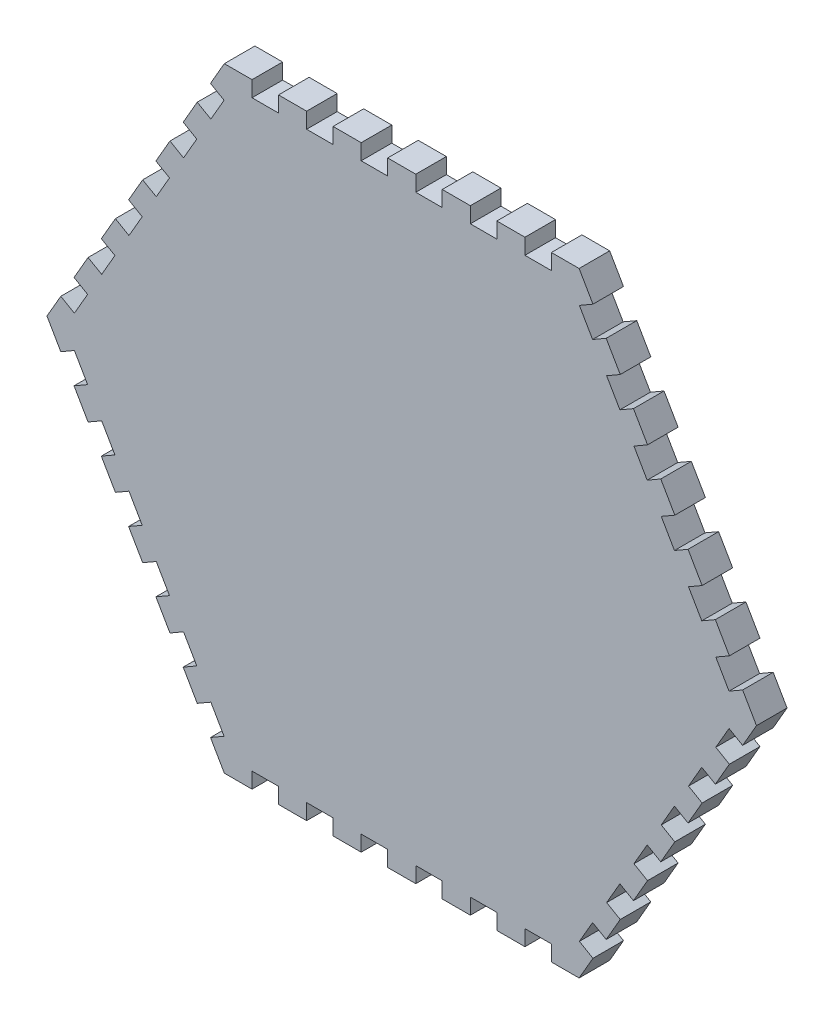
SolidWorks part; units mm, degrees
ref_plane "Piano frontale" through (0, 0, 0) normal (0, 0, 1) x (1, 0, 0)
ref_plane "Piano superiore" through (0, 0, 0) normal (0, 1, 0) x (1, 0, 0)
ref_plane "Piano destro" through (0, 0, 0) normal (1, 0, 0) x (0, 0, -1)
sketch "Schizzo1" plane through (0, 0, 0) normal (0, 0, 1) x (1, 0, 0)
  line L0 (-17.425, 53.4167) -> (-17.425, 56.2917)
  line L1 (32.5, 56.2917) -> (27.425, 56.2917)
  line L2 (-32.5, 56.2917) -> (-35.0375, 51.8966)
  line L3 (-65, 0) -> (-62.4625, -4.3951)
  line L4 (-32.5, -56.2917) -> (-27.425, -56.2917)
  line L5 (32.5, -56.2917) -> (35.0375, -51.8966)
  line L6 (65, 0) -> (62.4625, 4.3951)
  line L7 (-27.425, 53.4167) -> (-22.575, 53.4167)
  line L8 (-27.425, 53.4167) -> (-27.425, 56.2917)
  line L9 (-17.425, 56.2917) -> (-22.575, 56.2917)
  line L10 (-22.575, 53.4167) -> (-22.575, 56.2917)
  line L11 (-27.425, 53.4167) -> (-22.575, 56.2917) construction
  line L12 (-27.425, 56.2917) -> (-22.575, 53.4167) construction
  line L13 (-17.425, 53.4167) -> (-12.575, 53.4167)
  line L14 (-12.575, 53.4167) -> (-12.575, 56.2917)
  line L15 (-7.425, 53.4167) -> (-7.425, 56.2917)
  line L16 (-7.425, 53.4167) -> (-2.575, 53.4167)
  line L17 (-2.575, 53.4167) -> (-2.575, 56.2917)
  line L18 (2.575, 53.4167) -> (2.575, 56.2917)
  line L19 (2.575, 53.4167) -> (7.425, 53.4167)
  line L20 (7.425, 53.4167) -> (7.425, 56.2917)
  line L21 (12.575, 53.4167) -> (12.575, 56.2917)
  line L22 (12.575, 53.4167) -> (17.425, 53.4167)
  line L23 (17.425, 53.4167) -> (17.425, 56.2917)
  line L24 (22.575, 53.4167) -> (22.575, 56.2917)
  line L25 (22.575, 53.4167) -> (27.425, 53.4167)
  line L26 (27.425, 53.4167) -> (27.425, 56.2917)
  line L27 (32.5477, 50.4591) -> (35.0375, 51.8966)
  line L28 (32.5477, 50.4591) -> (34.9727, 46.2588)
  line L29 (34.9727, 46.2588) -> (37.4625, 47.6963)
  line L30 (37.5477, 41.7988) -> (40.0375, 43.2363)
  line L31 (37.5477, 41.7988) -> (39.9727, 37.5986)
  line L32 (39.9727, 37.5986) -> (42.4625, 39.0361)
  line L33 (42.5477, 33.1386) -> (45.0375, 34.5761)
  line L34 (42.5477, 33.1386) -> (44.9727, 28.9383)
  line L35 (44.9727, 28.9383) -> (47.4625, 30.3758)
  line L36 (47.5477, 24.4783) -> (50.0375, 25.9158)
  line L37 (47.5477, 24.4783) -> (49.9727, 20.2781)
  line L38 (49.9727, 20.2781) -> (52.4625, 21.7156)
  line L39 (52.5477, 15.8181) -> (55.0375, 17.2556)
  line L40 (52.5477, 15.8181) -> (54.9727, 11.6178)
  line L41 (54.9727, 11.6178) -> (57.4625, 13.0553)
  line L42 (57.5477, 7.1578) -> (60.0375, 8.5953)
  line L43 (57.5477, 7.1578) -> (59.9727, 2.9576)
  line L44 (59.9727, 2.9576) -> (62.4625, 4.3951)
  line L45 (59.9727, -2.9576) -> (62.4625, -4.3951)
  line L46 (59.9727, -2.9576) -> (57.5477, -7.1578)
  line L47 (57.5477, -7.1578) -> (60.0375, -8.5953)
  line L48 (54.9727, -11.6178) -> (57.4625, -13.0553)
  line L49 (54.9727, -11.6178) -> (52.5477, -15.8181)
  line L50 (52.5477, -15.8181) -> (55.0375, -17.2556)
  line L51 (49.9727, -20.2781) -> (52.4625, -21.7156)
  line L52 (49.9727, -20.2781) -> (47.5477, -24.4783)
  line L53 (47.5477, -24.4783) -> (50.0375, -25.9158)
  line L54 (44.9727, -28.9383) -> (47.4625, -30.3758)
  line L55 (44.9727, -28.9383) -> (42.5477, -33.1386)
  line L56 (42.5477, -33.1386) -> (45.0375, -34.5761)
  line L57 (39.9727, -37.5986) -> (42.4625, -39.0361)
  line L58 (39.9727, -37.5986) -> (37.5477, -41.7988)
  line L59 (37.5477, -41.7988) -> (40.0375, -43.2363)
  line L60 (34.9727, -46.2588) -> (37.4625, -47.6963)
  line L61 (34.9727, -46.2588) -> (32.5477, -50.4591)
  line L62 (32.5477, -50.4591) -> (35.0375, -51.8966)
  line L63 (27.425, -53.4167) -> (27.425, -56.2917)
  line L64 (27.425, -53.4167) -> (22.575, -53.4167)
  line L65 (22.575, -53.4167) -> (22.575, -56.2917)
  line L66 (17.425, -53.4167) -> (17.425, -56.2917)
  line L67 (17.425, -53.4167) -> (12.575, -53.4167)
  line L68 (12.575, -53.4167) -> (12.575, -56.2917)
  line L69 (7.425, -53.4167) -> (7.425, -56.2917)
  line L70 (7.425, -53.4167) -> (2.575, -53.4167)
  line L71 (2.575, -53.4167) -> (2.575, -56.2917)
  line L72 (-2.575, -53.4167) -> (-2.575, -56.2917)
  line L73 (-2.575, -53.4167) -> (-7.425, -53.4167)
  line L74 (-7.425, -53.4167) -> (-7.425, -56.2917)
  line L75 (-12.575, -53.4167) -> (-12.575, -56.2917)
  line L76 (-12.575, -53.4167) -> (-17.425, -53.4167)
  line L77 (-17.425, -53.4167) -> (-17.425, -56.2917)
  line L78 (-22.575, -53.4167) -> (-22.575, -56.2917)
  line L79 (-22.575, -53.4167) -> (-27.425, -53.4167)
  line L80 (-27.425, -53.4167) -> (-27.425, -56.2917)
  line L81 (-32.5477, -50.4591) -> (-35.0375, -51.8966)
  line L82 (-32.5477, -50.4591) -> (-34.9727, -46.2588)
  line L83 (-34.9727, -46.2588) -> (-37.4625, -47.6963)
  line L84 (-37.5477, -41.7988) -> (-40.0375, -43.2363)
  line L85 (-37.5477, -41.7988) -> (-39.9727, -37.5986)
  line L86 (-39.9727, -37.5986) -> (-42.4625, -39.0361)
  line L87 (-42.5477, -33.1386) -> (-45.0375, -34.5761)
  line L88 (-42.5477, -33.1386) -> (-44.9727, -28.9383)
  line L89 (-44.9727, -28.9383) -> (-47.4625, -30.3758)
  line L90 (-47.5477, -24.4783) -> (-50.0375, -25.9158)
  line L91 (-47.5477, -24.4783) -> (-49.9727, -20.2781)
  line L92 (-49.9727, -20.2781) -> (-52.4625, -21.7156)
  line L93 (-52.5477, -15.8181) -> (-55.0375, -17.2556)
  line L94 (-52.5477, -15.8181) -> (-54.9727, -11.6178)
  line L95 (-54.9727, -11.6178) -> (-57.4625, -13.0553)
  line L96 (-57.5477, -7.1578) -> (-60.0375, -8.5953)
  line L97 (-57.5477, -7.1578) -> (-59.9727, -2.9576)
  line L98 (-59.9727, -2.9576) -> (-62.4625, -4.3951)
  line L99 (-59.9727, 2.9576) -> (-62.4625, 4.3951)
  line L100 (-59.9727, 2.9576) -> (-57.5477, 7.1578)
  line L101 (-57.5477, 7.1578) -> (-60.0375, 8.5953)
  line L102 (-54.9727, 11.6178) -> (-57.4625, 13.0553)
  line L103 (-54.9727, 11.6178) -> (-52.5477, 15.8181)
  line L104 (-52.5477, 15.8181) -> (-55.0375, 17.2556)
  line L105 (-49.9727, 20.2781) -> (-52.4625, 21.7156)
  line L106 (-49.9727, 20.2781) -> (-47.5477, 24.4783)
  line L107 (-47.5477, 24.4783) -> (-50.0375, 25.9158)
  line L108 (-44.9727, 28.9383) -> (-47.4625, 30.3758)
  line L109 (-44.9727, 28.9383) -> (-42.5477, 33.1386)
  line L110 (-42.5477, 33.1386) -> (-45.0375, 34.5761)
  line L111 (-39.9727, 37.5986) -> (-42.4625, 39.0361)
  line L112 (-39.9727, 37.5986) -> (-37.5477, 41.7988)
  line L113 (-37.5477, 41.7988) -> (-40.0375, 43.2363)
  line L114 (-34.9727, 46.2588) -> (-37.4625, 47.6963)
  line L115 (-34.9727, 46.2588) -> (-32.5477, 50.4591)
  line L116 (-32.5477, 50.4591) -> (-35.0375, 51.8966)
  line L117 (-27.425, 56.2917) -> (-32.5, 56.2917)
  line L118 (-7.425, 56.2917) -> (-12.575, 56.2917)
  line L119 (2.575, 56.2917) -> (-2.575, 56.2917)
  line L120 (12.575, 56.2917) -> (7.425, 56.2917)
  line L121 (22.575, 56.2917) -> (17.425, 56.2917)
  line L122 (35.0375, 51.8966) -> (32.5, 56.2917)
  line L123 (40.0375, 43.2363) -> (37.4625, 47.6963)
  line L124 (45.0375, 34.5761) -> (42.4625, 39.0361)
  line L125 (50.0375, 25.9158) -> (47.4625, 30.3758)
  line L126 (55.0375, 17.2556) -> (52.4625, 21.7156)
  line L127 (60.0375, 8.5953) -> (57.4625, 13.0553)
  line L128 (62.4625, -4.3951) -> (65, 0)
  line L129 (57.4625, -13.0553) -> (60.0375, -8.5953)
  line L130 (52.4625, -21.7156) -> (55.0375, -17.2556)
  line L131 (47.4625, -30.3758) -> (50.0375, -25.9158)
  line L132 (42.4625, -39.0361) -> (45.0375, -34.5761)
  line L133 (37.4625, -47.6963) -> (40.0375, -43.2363)
  line L134 (27.425, -56.2917) -> (32.5, -56.2917)
  line L135 (17.425, -56.2917) -> (22.575, -56.2917)
  line L136 (7.425, -56.2917) -> (12.575, -56.2917)
  line L137 (-2.575, -56.2917) -> (2.575, -56.2917)
  line L138 (-12.575, -56.2917) -> (-7.425, -56.2917)
  line L139 (-22.575, -56.2917) -> (-17.425, -56.2917)
  line L140 (-35.0375, -51.8966) -> (-32.5, -56.2917)
  line L141 (-40.0375, -43.2363) -> (-37.4625, -47.6963)
  line L142 (-45.0375, -34.5761) -> (-42.4625, -39.0361)
  line L143 (-50.0375, -25.9158) -> (-47.4625, -30.3758)
  line L144 (-55.0375, -17.2556) -> (-52.4625, -21.7156)
  line L145 (-60.0375, -8.5953) -> (-57.4625, -13.0553)
  line L146 (-62.4625, 4.3951) -> (-65, 0)
  line L147 (-57.4625, 13.0553) -> (-60.0375, 8.5953)
  line L148 (-52.4625, 21.7156) -> (-55.0375, 17.2556)
  line L149 (-47.4625, 30.3758) -> (-50.0375, 25.9158)
  line L150 (-42.4625, 39.0361) -> (-45.0375, 34.5761)
  line L151 (-37.4625, 47.6963) -> (-40.0375, 43.2363)
  circle A0 centre (0, 0) radius 56.2917 construction
  point P1 (-25, 54.8542)
  point P156 (0, 0)
  dimension "D1" = 65
  dimension "D2" = 4.85
  dimension "D3" = 2.875
  dimension "D6" = 5.15
  dimension "D4" = 6
  dimension "D5" = 6
extrude "Estrusione-Estrusione1" add sketch "Schizzo1" along normal blind 5.6
equation "\"side\"= 65'hexagon side"
equation "\"joint whidth\"= 5"
equation "\"mat thickness\"= 5.6"
equation "\"kerf\"= 0.075"
equation "\"D1@Schizzo1\"= \"side\""
equation "\"D2@Schizzo1\" = \"joint whidth\" - ( 2 * \"kerf\" )"
equation "\"D3@Schizzo1\"= ( \"mat thickness\" / 2 ) + \"kerf\""
equation "\"D6@Schizzo1\"= \"joint whidth\" + ( 2 * \"kerf\" )"
